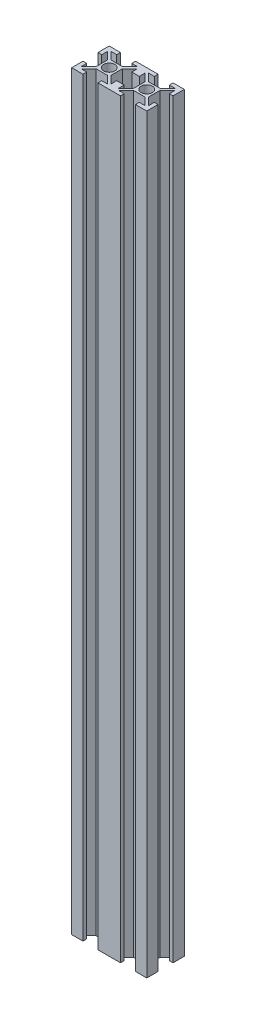
SolidWorks part; units mm, degrees
material "1060 Alloy"
ref_plane "Front Plane" through (0, 0, 0) normal (0, 0, 1) x (1, 0, 0)
ref_plane "Top Plane" through (0, 0, 0) normal (0, 1, 0) x (1, 0, 0)
ref_plane "Right Plane" through (0, 0, 0) normal (1, 0, 0) x (0, 0, -1)
sketch "2020 sketch" plane through (0, 0, 0) normal (0, 1, 0) x (1, 0, 0)
  line L0 (-4, 10) -> (-4, 8)
  line L1 (-10, 10) -> (-4, 10)
  line L2 (-10, 10) -> (-10, 4)
  line L3 (-10, -10) -> (-4, -10)
  line L4 (10, 10) -> (10, 4)
  line L5 (-10, 10) -> (10, -10) construction
  line L6 (-10, -10) -> (10, 10) construction
  line L7 (-4, 8) -> (-7, 8)
  line L8 (-7, 8) -> (-3, 4)
  line L9 (-3, 4) -> (3, 4)
  line L10 (3, 4) -> (7, 8)
  line L11 (7, 8) -> (4, 8)
  line L12 (4, 8) -> (4, 10)
  line L13 (4, 3) -> (4, -3)
  line L14 (8, 7) -> (4, 3)
  line L15 (8, 4) -> (8, 7)
  line L16 (10, 4) -> (8, 4)
  line L17 (8, -4) -> (10, -4)
  line L18 (8, -7) -> (8, -4)
  line L19 (4, -3) -> (8, -7)
  line L20 (3, -4) -> (-3, -4)
  line L21 (7, -8) -> (3, -4)
  line L22 (4, -8) -> (7, -8)
  line L23 (4, -10) -> (4, -8)
  line L24 (-4, -8) -> (-4, -10)
  line L25 (-7, -8) -> (-4, -8)
  line L26 (-3, -4) -> (-7, -8)
  line L27 (-4, -3) -> (-4, 3)
  line L28 (-8, -7) -> (-4, -3)
  line L29 (-8, -4) -> (-8, -7)
  line L30 (-10, -4) -> (-8, -4)
  line L31 (-8, 4) -> (-10, 4)
  line L32 (-8, 7) -> (-8, 4)
  line L33 (-4, 3) -> (-8, 7)
  line L34 (-10, -4) -> (-10, -10)
  line L35 (10, -4) -> (10, -10)
  line L36 (4, 10) -> (10, 10)
  line L37 (4, -10) -> (10, -10)
  circle A0 centre (0, 0) radius 3
  point P0 (0, 0)
  point P14 (4, 9)
  point P42 (0, 0)
  dimension "D9" = 6
  dimension "D1" = 20
  dimension "D2" = 20
  dimension "D3" = 8
  dimension "D4" = 6
  dimension "D5" = 6
  dimension "D6" = 2
  dimension "D7" = 4
  dimension "D8" = 4
extrude "Boss-Extrude1" add sketch "2020 sketch" along normal blind 400 contours A0 | L28 L27 L33 L32 L31 L2 L1 L0 L7 L8 L9 L10 L11 L12 L36 L4 L16 L15 L14 L13 L19 L18 L17 L35 L37 L23 L22 L21 L20 L26 L25 L24 L3 L34 L30 L29
mirror "Mirror1" about plane through (10, 400, 4) normal (1, 0, 0) of "Boss-Extrude1"
